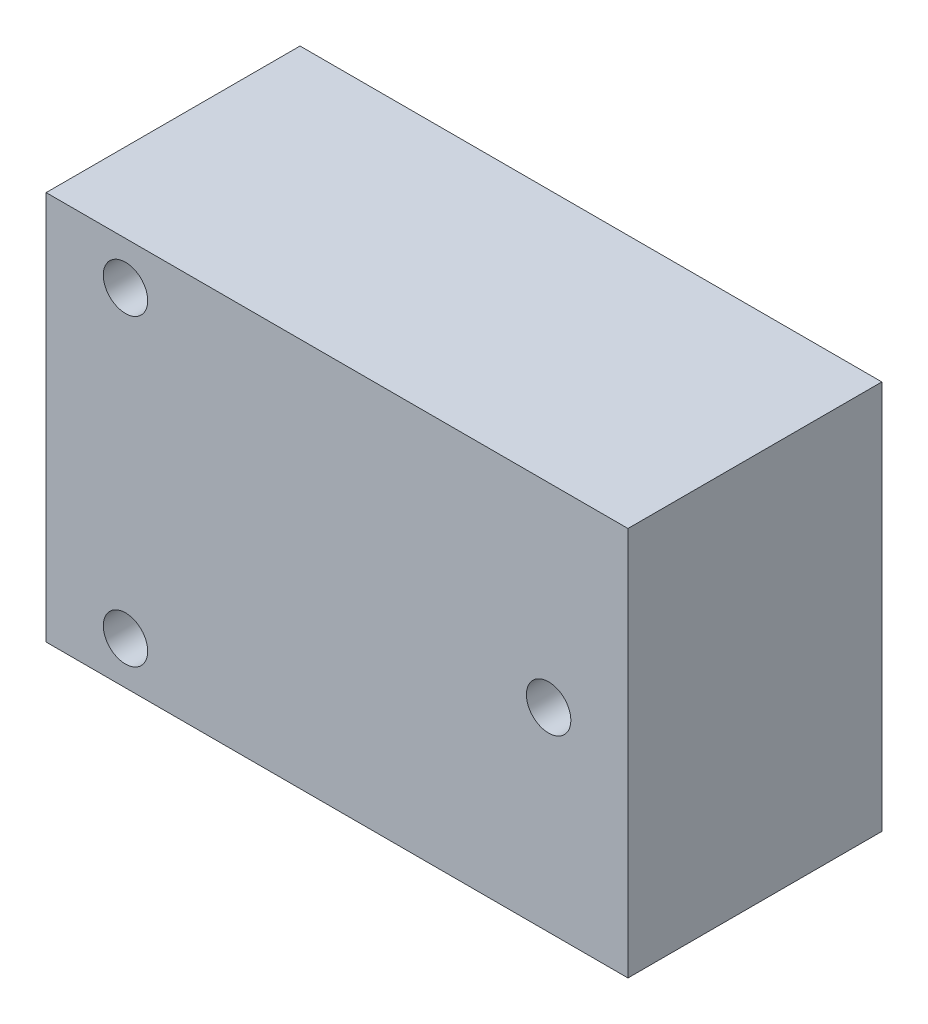
SolidWorks part; units mm, degrees
ref_plane "前视基准面" through (0, 0, 0) normal (0, 0, 1) x (1, 0, 0)
ref_plane "上视基准面" through (0, 0, 0) normal (0, 1, 0) x (1, 0, 0)
ref_plane "右视基准面" through (0, 0, 0) normal (1, 0, 0) x (0, 0, -1)
other "Configuration Table"
sketch "草图1" plane through (0, 0, 0) normal (0, 0, 1) x (1, 0, 0)
  line L0 (55, 0) -> (-55, 0) construction
  line L1 (27.5, 18.4) -> (-27.5, 18.4)
  line L2 (27.5, 18.4) -> (27.5, -18.4)
  line L3 (27.5, -18.4) -> (-27.5, -18.4)
  line L4 (-27.5, 18.4) -> (-27.5, -18.4)
  line L5 (27.5, 18.4) -> (-27.5, -18.4) construction
  line L6 (27.5, -18.4) -> (-27.5, 18.4) construction
  circle A0 centre (-20, 14.35) radius 2.1
  circle A1 centre (20, 0) radius 2.1
  circle A2 centre (-20, -14.35) radius 2.1
  point P0 (0, 0)
  dimension "D3" = 14.35
  dimension "D4" = 4.2
  dimension "D5" = 20
  dimension "D6" = 20
  dimension "D7" = 4.2
  dimension "D8" = 18.4
  dimension "D1" = 36.8
  dimension "D2" = 55
extrude "凸台-拉伸1" add sketch "草图1" along normal blind 24
